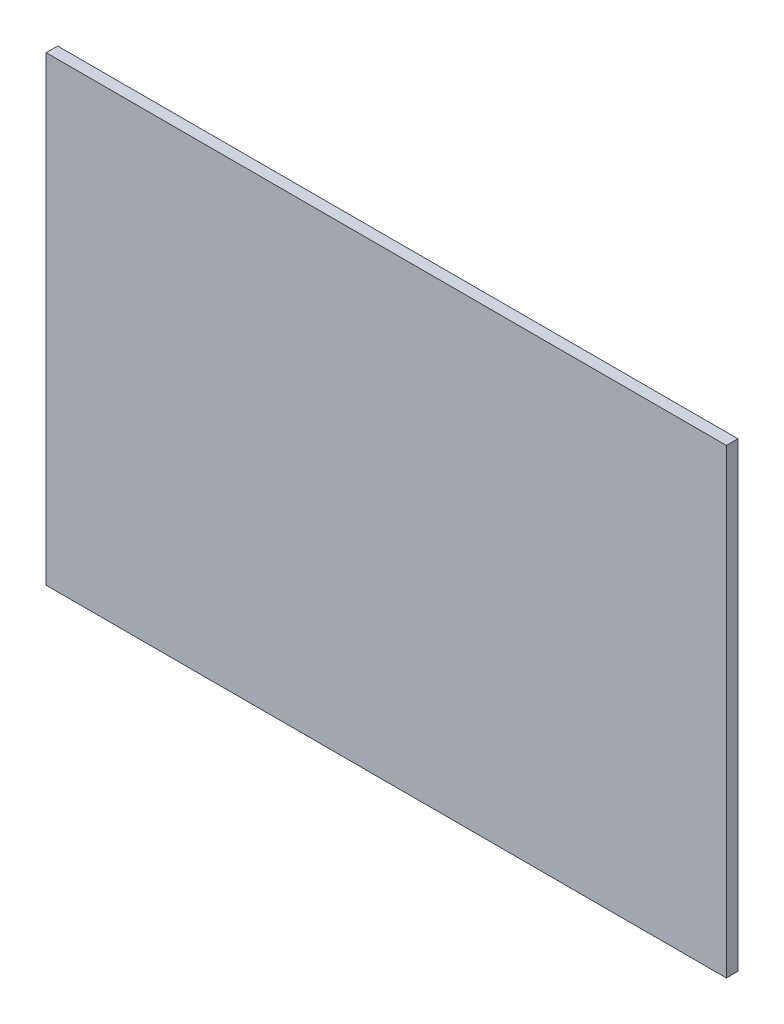
SolidWorks part; units mm, degrees
material "Pine"
ref_plane "Front Plane" through (0, 0, 0) normal (0, 0, 1) x (1, 0, 0)
ref_plane "Top Plane" through (0, 0, 0) normal (0, 1, 0) x (1, 0, 0)
ref_plane "Right Plane" through (0, 0, 0) normal (1, 0, 0) x (0, 0, -1)
sketch "Sketch1" plane through (0, 0, 0) normal (0, 0, 1) x (1, 0, 0)
  line L1 (-147.5, 100) -> (147.5, 100)
  line L2 (-147.5, 100) -> (-147.5, -100)
  line L3 (-147.5, -100) -> (147.5, -100)
  line L4 (147.5, 100) -> (147.5, -100)
  line L5 (-147.5, 100) -> (147.5, -100) construction
  line L6 (-147.5, -100) -> (147.5, 100) construction
  point P0 (0, 0)
  dimension "D1" = 295
  dimension "D2" = 200
extrude "Boss-Extrude1" add sketch "Sketch1" along normal blind 5
